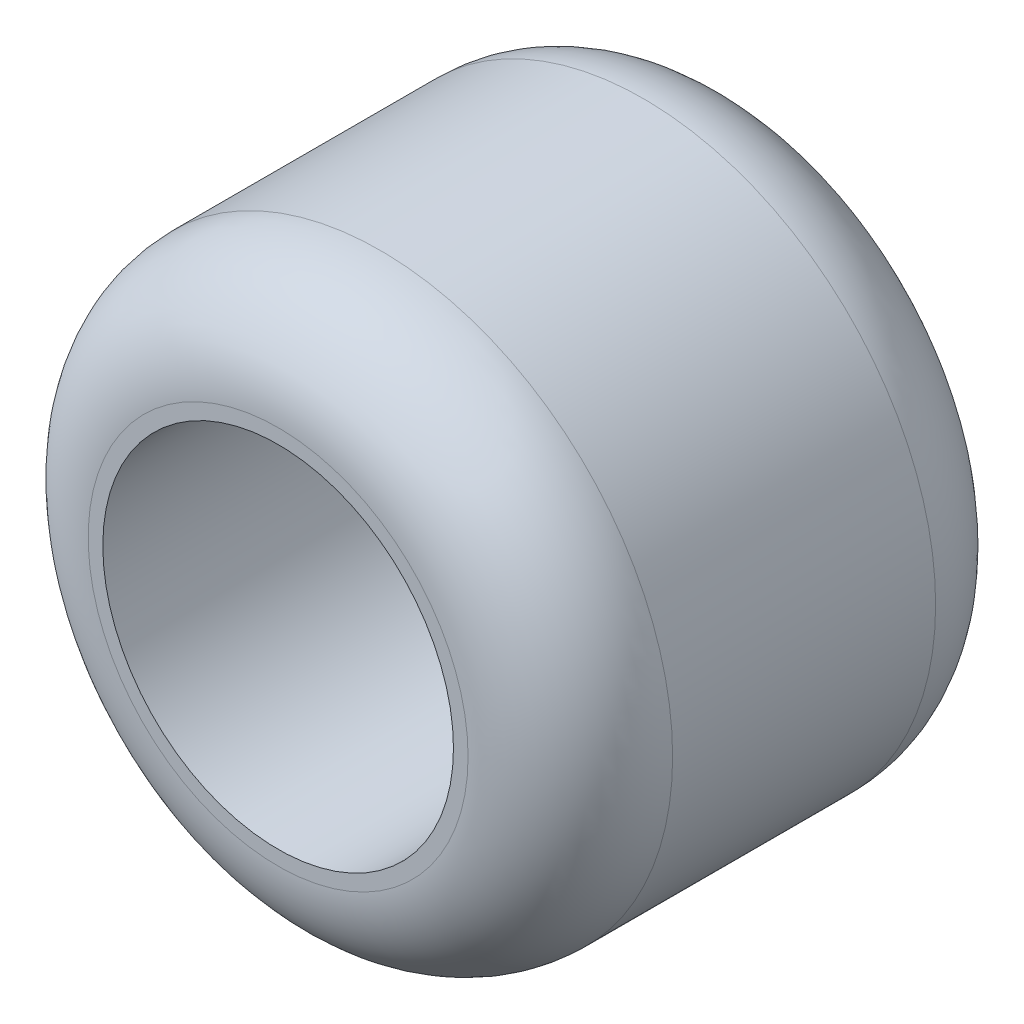
SolidWorks part; units mm, degrees
ref_plane "Front Plane" through (0, 0, 0) normal (0, 0, 1) x (1, 0, 0)
ref_plane "Top Plane" through (0, 0, 0) normal (0, 1, 0) x (1, 0, 0)
ref_plane "Right Plane" through (0, 0, 0) normal (1, 0, 0) x (0, 0, -1)
sketch "Sketch1" plane through (0, 0, 0) normal (0, 0, 1) x (1, 0, 0)
  circle A0 centre (0, 0) radius 5
  dimension "D1" = 10
extrude "Boss-Extrude1" add sketch "Sketch1" along normal blind 8
sketch "Sketch2" plane through (0, 0, 8) normal (0, 0, 1) x (1, 0, 0)
  circle A0 centre (0, 0) radius 3
  dimension "D1" = 6
extrude "Cut-Extrude1" cut sketch "Sketch2" against normal blind 8
fillet "Fillet1" radius 1.75 2 edges at (5, 0, 0) (5, 0, 8)
